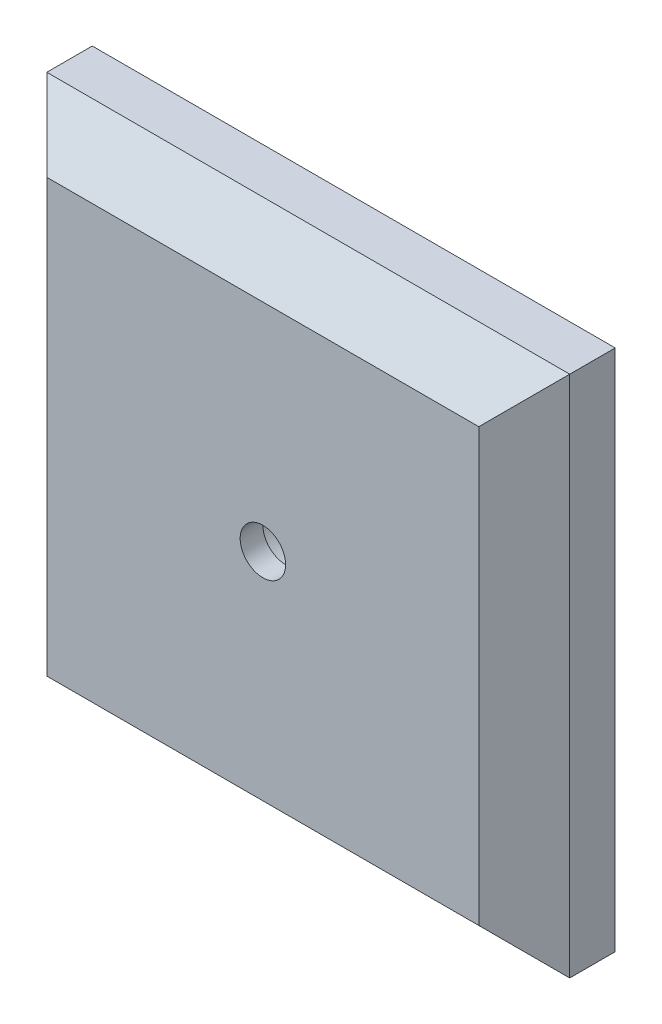
SolidWorks part; units mm, degrees
material "Plain Carbon Steel"
ref_plane "Front Plane" through (0, 0, 0) normal (0, 0, 1) x (1, 0, 0)
ref_plane "Top Plane" through (0, 0, 0) normal (0, 1, 0) x (1, 0, 0)
ref_plane "Right Plane" through (0, 0, 0) normal (1, 0, 0) x (0, 0, -1)
sketch "Sketch2" plane through (0, 0, 0) normal (0, 0, 1) x (1, 0, 0)
  line L1 (-38.1336, 38.0298) -> (34.8914, 38.0298)
  line L2 (-38.1336, 38.0298) -> (-38.1336, -34.9952)
  line L3 (-38.1336, -34.9952) -> (34.8914, -34.9952)
  line L4 (34.8914, 38.0298) -> (34.8914, -34.9952)
  dimension "D1" = 73.025
extrude "Boss-Extrude1" add sketch "Sketch2" along normal blind 6.35
sketch "Sketch3" plane through (0, 0, 6.35) normal (0, 0, 1) x (1, 0, 0)
  line L1 (-38.1336, 38.0298) -> (34.8914, 38.0298)
  line L2 (-38.1336, 38.0298) -> (-38.1336, -34.9952)
  line L3 (-38.1336, -34.9952) -> (34.8914, -34.9952)
  line L4 (34.8914, 38.0298) -> (34.8914, -34.9952)
extrude "Boss-Extrude2" add sketch "Sketch3" along normal blind 6.35
sketch "Sketch4" plane through (0, 0, 0) normal (0, 0, -1) x (-1, 0, 0)
  line L0 (-34.8914, 38.0298) -> (38.1336, 38.0298) construction
  line L2 (38.1336, 38.0298) -> (38.1336, -34.9952) construction
  line L3 (-34.8914, -34.9952) -> (-34.8914, 38.0298) construction
  line L4 (-34.8914, -34.9952) -> (-34.8914, 38.0298) construction
  circle A0 centre (1.6084, 1.5046) radius 6.35
  dimension "D1" = 12.7
  dimension "D2" = 36.5252
  dimension "D3" = 36.5252
sketch "Sketch8" plane through (0, 0, 12.7) normal (0, 0, 1) x (1, 0, 0)
  circle A0 centre (-1.6084, 1.5046) radius 3.175
  dimension "D1" = 6.35
extrude "Cut-Extrude3" cut sketch "Sketch8" against normal blind 3.175
extrude "Cut-Extrude4" cut sketch "Sketch4" against normal blind 9.525 contours A0
chamfer "Chamfer1" distance 6.35 4 edges at (-1.6211, -34.9952, 12.7) (34.8914, 1.5173, 12.7) (-1.6211, 38.0298, 12.7) (-38.1336, 1.5173, 12.7)
